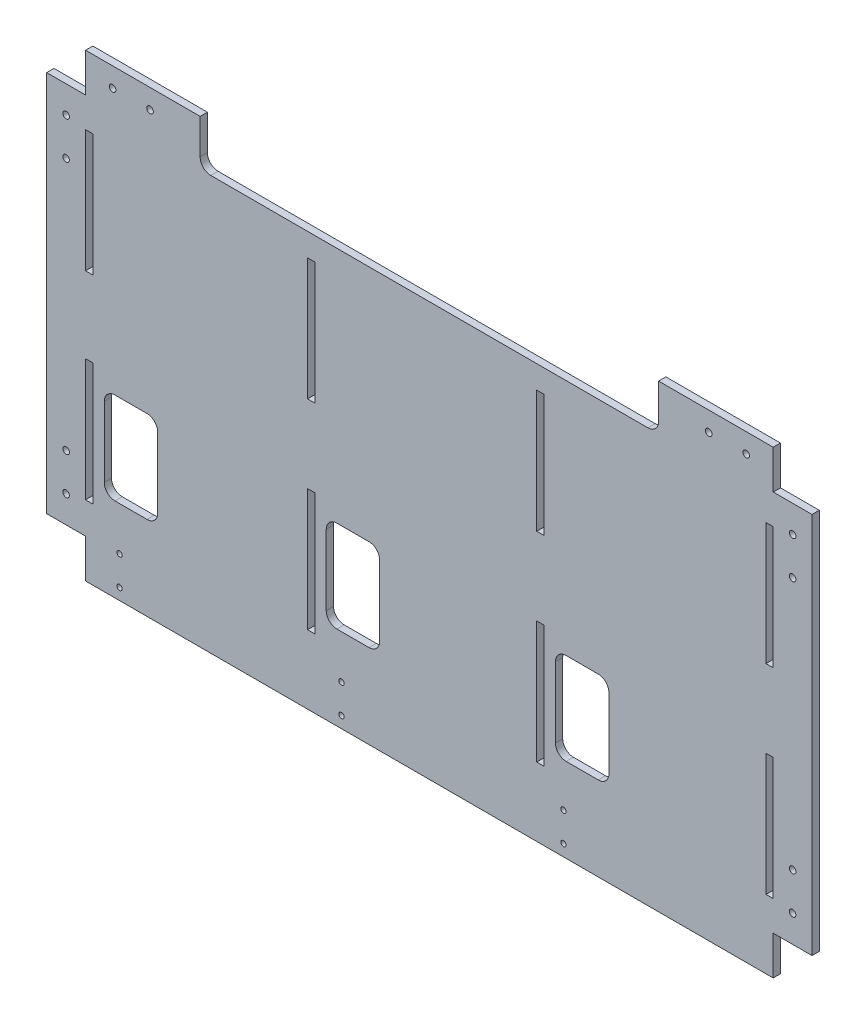
SolidWorks part; units mm, degrees
ref_plane "前基準面" through (0, 0, 0) normal (0, 0, 1) x (1, 0, 0)
ref_plane "上基準面" through (0, 0, 0) normal (0, 1, 0) x (1, 0, 0)
ref_plane "右基準面" through (0, 0, 0) normal (1, 0, 0) x (0, 0, -1)
sketch "草圖1" plane through (0, 0, 0) normal (0, 0, 1) x (1, 0, 0)
  line L1 (-250.4, 150.4) -> (250.4, 150.4)
  line L2 (-250.4, 150.4) -> (-250.4, -150.4)
  line L3 (-250.4, -150.4) -> (250.4, -150.4)
  line L4 (250.4, 150.4) -> (250.4, -150.4)
  line L5 (-250.4, 150.4) -> (250.4, -150.4) construction
  line L6 (-250.4, -150.4) -> (250.4, 150.4) construction
  point P0 (0, 0)
  dimension "D1" = 500.8
  dimension "D2" = 300.8
extrude "填料-伸長1" add sketch "草圖1" along normal blind 4.75 contours L1 L4 L3 L2
sketch "草圖2" plane through (0, 0, 0) normal (0, 0, -1) x (-1, 0, 0)
  line L0 (-225, 125) -> (-225, -125) construction
  line L1 (-250.4, 150.4) -> (-225, 150.4)
  line L2 (-250.4, 150.4) -> (-250.4, 125)
  line L3 (-250.4, 125) -> (-225, 125)
  line L4 (-225, 150.4) -> (-225, 125)
  line L5 (-250.4, -150.4) -> (-225, -150.4)
  line L6 (-250.4, -150.4) -> (-250.4, -125)
  line L7 (-250.4, -125) -> (-225, -125)
  line L8 (-225, -150.4) -> (-225, -125)
  line L9 (250.4, 150.4) -> (225, 150.4)
  line L10 (250.4, 150.4) -> (250.4, 125)
  line L12 (225, 150.4) -> (225, 125)
  line L13 (250.4, -150.4) -> (225, -150.4)
  line L14 (250.4, -150.4) -> (250.4, -125)
  line L16 (225, -150.4) -> (225, -125)
  line L17 (225, 125) -> (225, -125) construction
  line L18 (250.4, 150.4) -> (-250.4, 150.4) construction
  line L19 (-225, 105.4) -> (-220.25, 105.4)
  line L20 (-225, 105.4) -> (-225, 25.4)
  line L21 (-225, 25.4) -> (-220.25, 25.4)
  line L22 (-220.25, 105.4) -> (-220.25, 25.4)
  line L23 (-225, -25.4) -> (-220.25, -25.4)
  line L24 (-225, -25.4) -> (-225, -105.4)
  line L25 (-225, -105.4) -> (-220.25, -105.4)
  line L26 (-220.25, -25.4) -> (-220.25, -105.4)
  line L27 (250.4, -150.4) -> (-250.4, -150.4) construction
  line L44 (225, 105.4) -> (225, 25.4)
  line L45 (225, 105.4) -> (220.25, 105.4)
  line L46 (220.25, 105.4) -> (220.25, 25.4)
  line L47 (225, 25.4) -> (220.25, 25.4)
  line L48 (225, -24.4) -> (225, -104.4)
  line L49 (225, -24.4) -> (220.25, -24.4)
  line L50 (220.25, -24.4) -> (220.25, -104.4)
  line L51 (225, -104.4) -> (220.25, -104.4)
  line L60 (-75, 105.4) -> (-75, 25.4)
  line L61 (-75, 25.4) -> (-70.25, 25.4)
  line L62 (-70.25, 105.4) -> (-70.25, 25.4)
  line L63 (-75, 105.4) -> (-70.25, 105.4)
  line L80 (75, 105.4) -> (75, 25.4)
  line L81 (75, 25.4) -> (79.75, 25.4)
  line L82 (79.75, 105.4) -> (79.75, 25.4)
  line L83 (75, 105.4) -> (79.75, 105.4)
  line L84 (-250.4, 0) -> (250.4, 0) construction
  line L85 (-250.4, 150.4) -> (-250.4, -150.4) construction
  line L86 (250.4, 150.4) -> (250.4, -150.4) construction
  line L89 (250.4, -125) -> (250.4, 125)
  line L91 (250.4, 125) -> (250.4, -125)
  line L92 (75, -105.4) -> (79.75, -105.4)
  line L93 (79.75, -105.4) -> (79.75, -25.4)
  line L94 (75, -25.4) -> (79.75, -25.4)
  line L95 (75, -105.4) -> (75, -25.4)
  line L105 (-75, -105.4) -> (-70.25, -105.4)
  line L106 (-70.25, -105.4) -> (-70.25, -25.4)
  line L107 (-75, -25.4) -> (-70.25, -25.4)
  line L108 (-75, -105.4) -> (-75, -25.4)
  line L109 (225, 125) -> (250.4, 125)
  line L110 (225, -125) -> (250.4, -125)
  dimension "D1" = 25.4
  dimension "D2" = 25.4
  dimension "D3" = 25.4
  dimension "D4" = 25.4
  dimension "D5" = 25.4
  dimension "D6" = 25.4
  dimension "D7" = 25.4
  dimension "D8" = 25.4
  dimension "D9" = 4.75
  dimension "D10" = 80
  dimension "D11" = 45
  dimension "D12" = 4.75
  dimension "D13" = 80
  dimension "D14" = 45
  dimension "D15" = 80
  dimension "D16" = 25.4
  dimension "D17" = 25.4
  dimension "D18" = 4.75
  dimension "D19" = 250
  dimension "D20" = 25.4
  dimension "D21" = 4.75
extrude "除料-伸長1" cut sketch "草圖2" against normal blind 25.4
sketch "草圖3" plane through (0, 0, 4.75) normal (0, 0, 1) x (1, 0, 0)
  circle A0 centre (-207.3, 137.7) radius 2.15
  circle A1 centre (-182.8, 137.7) radius 2.15
  circle A2 centre (182.8, 137.7) radius 2.15
  circle A3 centre (207.3, 137.7) radius 2.15
  circle A4 centre (237.7, 107.3) radius 2.15
  circle A5 centre (237.7, 82.8) radius 2.15
  circle A6 centre (237.7, -82.8) radius 2.15
  circle A7 centre (237.7, -107.3) radius 2.15
  circle A12 centre (-237.7, 107.3) radius 2.15
  circle A13 centre (-237.7, 82.8) radius 2.15
  circle A14 centre (-237.7, -82.8) radius 2.15
  circle A15 centre (-237.7, -107.3) radius 2.15
  dimension "D1" = 2
extrude "除料-伸長2" cut sketch "草圖3" against normal blind 5
sketch "草圖5" plane through (0, 0, 4.75) normal (0, 0, 1) x (1, 0, 0)
  line L0 (-75, 25.4) -> (-75, 105.4) construction
  line L1 (82.5, -35.4) -> (117.5, -35.4)
  line L2 (82.5, -35.4) -> (82.5, -95.4)
  line L3 (82.5, -95.4) -> (117.5, -95.4)
  line L4 (117.5, -35.4) -> (117.5, -95.4)
  line L5 (82.5, -35.4) -> (117.5, -95.4) construction
  line L6 (82.5, -95.4) -> (117.5, -35.4) construction
  line L7 (-67.5, -35.4) -> (-32.5, -35.4)
  line L8 (-67.5, -35.4) -> (-67.5, -95.4)
  line L9 (-67.5, -95.4) -> (-32.5, -95.4)
  line L10 (-32.5, -35.4) -> (-32.5, -95.4)
  line L11 (-67.5, -35.4) -> (-32.5, -95.4) construction
  line L12 (-67.5, -95.4) -> (-32.5, -35.4) construction
  line L13 (-212.75, -35.4) -> (-177.75, -35.4)
  line L14 (-212.75, -35.4) -> (-212.75, -95.4)
  line L15 (-212.75, -95.4) -> (-177.75, -95.4)
  line L16 (-177.75, -35.4) -> (-177.75, -95.4)
  line L17 (-212.75, -35.4) -> (-177.75, -95.4) construction
  line L18 (-212.75, -95.4) -> (-177.75, -35.4) construction
  line L20 (-220.25, -104.4) -> (-220.25, -24.4) construction
  line L21 (75, -25.4) -> (75, -105.4) construction
  line L22 (-225, 150.4) -> (225, 150.4) construction
  line L24 (225, 125) -> (225, 150.4) construction
  line L25 (-150, 150.4) -> (150, 150.4)
  line L26 (-150, 150.4) -> (-150, 120.4)
  line L27 (-150, 120.4) -> (150, 120.4)
  line L28 (150, 150.4) -> (150, 120.4)
  line L29 (-225, -150.4) -> (225, -150.4) construction
  point P0 (100, -65.4)
  point P5 (-50, -65.4)
  point P10 (-195.25, -65.4)
  dimension "D1" = 35
  dimension "D2" = 60
  dimension "D3" = 35
  dimension "D4" = 60
  dimension "D5" = 35
  dimension "D6" = 60
  dimension "D7" = 7.5
  dimension "D8" = 7.5
  dimension "D9" = 55
  dimension "D10" = 55
  dimension "D11" = 55
  dimension "D12" = 7.5
  dimension "D13" = 300
  dimension "D14" = 75
  dimension "D15" = 30
extrude "除料-伸長3" cut sketch "草圖5" against normal blind 10
fillet "圓角1" radius 7 14 edges at (-150, 120.4, 2.375) (150, 120.4, 2.375) (117.5, -35.4, 2.375) (82.5, -35.4, 2.375) (82.5, -95.4, 2.375) (117.5, -95.4, 2.375) (-32.5, -95.4, 2.375) (-67.5, -95.4, 2.375) (-32.5, -35.4, 2.375) (-67.5, -35.4, 2.375) (-177.75, -95.4, 2.375) (-212.75, -95.4, 2.375) (-212.75, -35.4, 2.375) (-177.75, -35.4, 2.375)
sketch "草圖6" plane through (0, 0, 4.75) normal (0, 0, 1) x (1, 0, 0)
  line L1 (-225, -150.4) -> (225, -150.4) construction
  line L2 (-220.25, -104.4) -> (-220.25, -24.4) construction
  circle A0 centre (-202.75, -142.9) radius 1.75
  circle A1 centre (-202.75, -123.9) radius 1.75
  circle A2 centre (-57.5, -142.9) radius 1.75
  circle A3 centre (-57.5, -123.9) radius 1.75
  circle A4 centre (87.75, -142.9) radius 1.75
  circle A5 centre (87.75, -123.9) radius 1.75
  dimension "D3" = 19
  dimension "D5" = 3.5
  dimension "D6" = 3.5
  dimension "D1" = 17.5
  dimension "D2" = 7.5
  dimension "D4" = 3
extrude "除料-伸長4" cut sketch "草圖6" against normal blind 10
